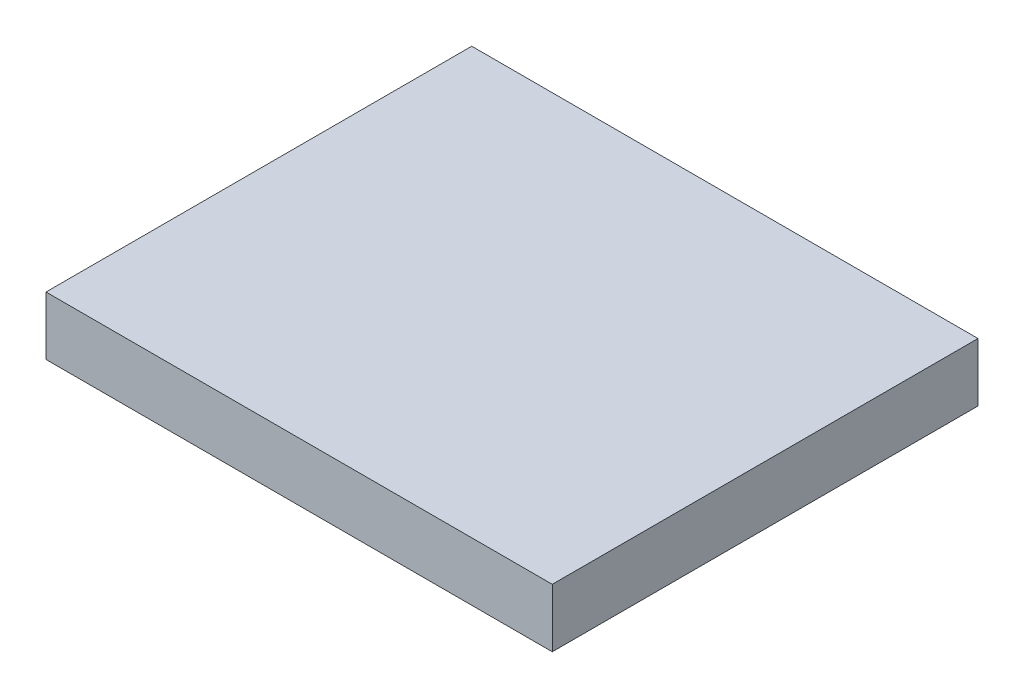
SolidWorks part; units mm, degrees
ref_plane "Front Plane" through (0, 0, 0) normal (0, 0, 1) x (1, 0, 0)
ref_plane "Top Plane" through (0, 0, 0) normal (0, 1, 0) x (1, 0, 0)
ref_plane "Right Plane" through (0, 0, 0) normal (1, 0, 0) x (0, 0, -1)
sketch "Sketch1" plane through (0, 0, 0) normal (0, 1, 0) x (1, 0, 0)
  line L1 (-110, 92.5) -> (110, 92.5)
  line L2 (-110, 92.5) -> (-110, -92.5)
  line L3 (-110, -92.5) -> (110, -92.5)
  line L4 (110, 92.5) -> (110, -92.5)
  point P0 (0, 0)
extrude "Boss-Extrude1" add sketch "Sketch1" along normal blind 25.4
